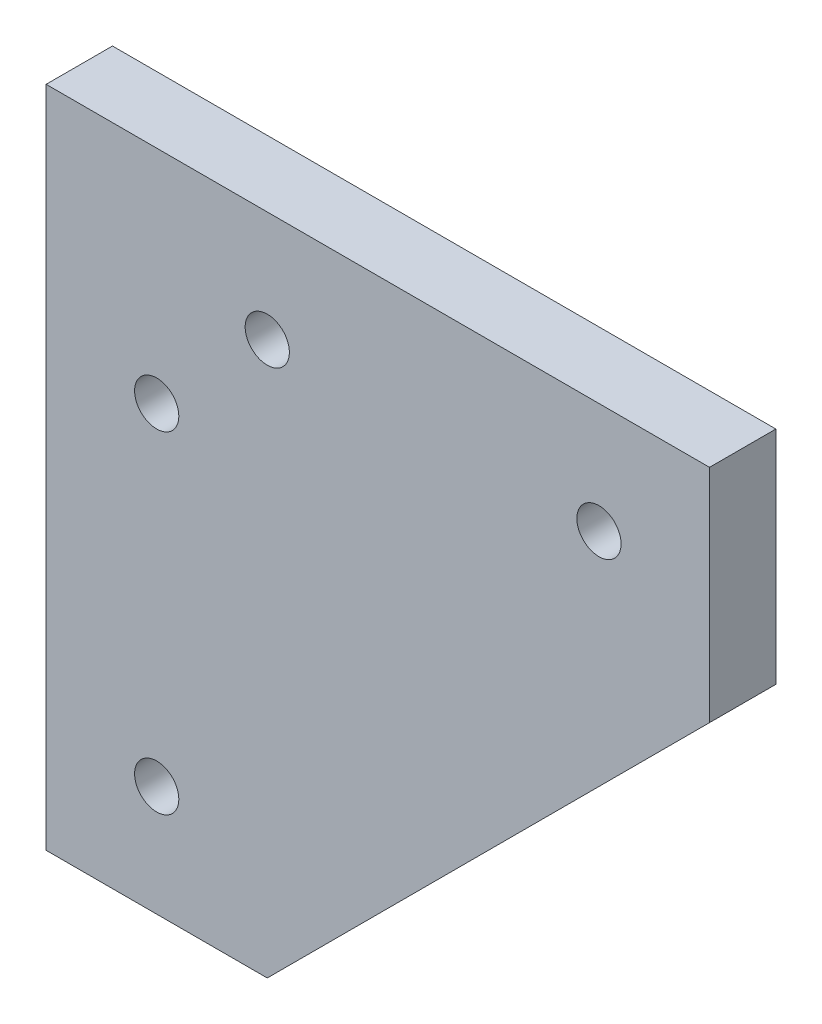
SolidWorks part; units mm, degrees
ref_plane "Front Plane" through (0, 0, 0) normal (0, 0, 1) x (1, 0, 0)
ref_plane "Top Plane" through (0, 0, 0) normal (0, 1, 0) x (1, 0, 0)
ref_plane "Right Plane" through (0, 0, 0) normal (1, 0, 0) x (0, 0, -1)
sketch "Sketch1" plane through (0, 0, 0) normal (0, 0, 1) x (1, 0, 0)
  line L0 (20, -60) -> (60, -20)
  line L1 (0, 0) -> (60, 0)
  line L2 (0, 0) -> (0, -60)
  line L3 (0, -60) -> (20, -60)
  line L4 (60, 0) -> (60, -20)
  line L5 (10, -60) -> (10, -50) construction
  line L6 (10, -50) -> (10, -20) construction
  line L7 (10, -20) -> (10, -10) construction
  line L8 (10, -10) -> (20, -10) construction
  line L9 (20, -10) -> (50, -10) construction
  line L10 (50, -10) -> (60, -10) construction
  circle A0 centre (50, -10) radius 2
  circle A1 centre (20, -10) radius 2
  circle A2 centre (10, -50) radius 2
  circle A3 centre (10, -20) radius 2
  dimension "D3" = 4
  dimension "D1" = 60
  dimension "D2" = 20
  dimension "D4" = 10
  dimension "D5" = 20
  dimension "D6" = 20
  dimension "D7" = 10
extrude "Boss-Extrude1" add sketch "Sketch1" along normal blind 6
